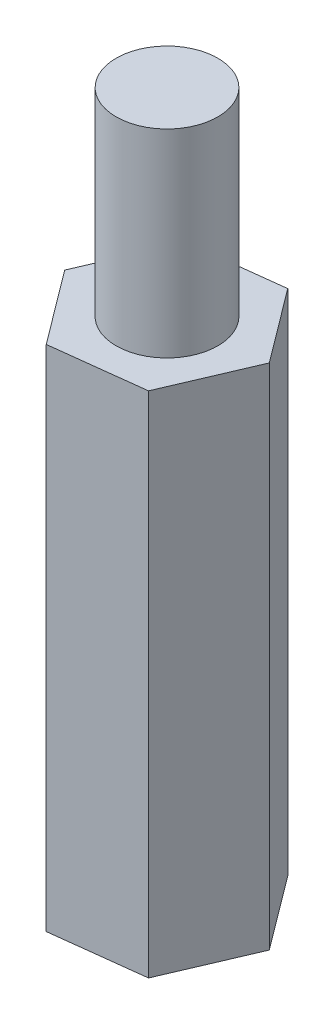
SolidWorks part; units mm, degrees
ref_plane "Front Plane" through (0, 0, 0) normal (0, 0, 1) x (1, 0, 0)
ref_plane "Top Plane" through (0, 0, 0) normal (0, 1, 0) x (1, 0, 0)
ref_plane "Right Plane" through (0, 0, 0) normal (1, 0, 0) x (0, 0, -1)
sketch "Sketch1" plane through (0, 0, 0) normal (0, 1, 0) x (1, 0, 0)
  line L1 (-2.6943, -0.3228) -> (-1.0676, -2.4947)
  line L2 (-1.0676, -2.4947) -> (1.6267, -2.1719)
  line L3 (1.6267, -2.1719) -> (2.6943, 0.3228)
  line L4 (2.6943, 0.3228) -> (1.0676, 2.4947)
  line L5 (1.0676, 2.4947) -> (-1.6267, 2.1719)
  line L6 (-1.6267, 2.1719) -> (-2.6943, -0.3228)
  circle A0 centre (0, 0) radius 2.35 construction
  circle A1 centre (0, 0) radius 1.5
extrude "Boss-Extrude1" add sketch "Sketch1" along normal blind 15
sketch "Sketch2" plane through (0, 15, 0) normal (0, 1, 0) x (1, 0, 0)
  circle A0 centre (0, 0) radius 1.5
extrude "Boss-Extrude2" add sketch "Sketch2" along normal blind 5.85 separate body
